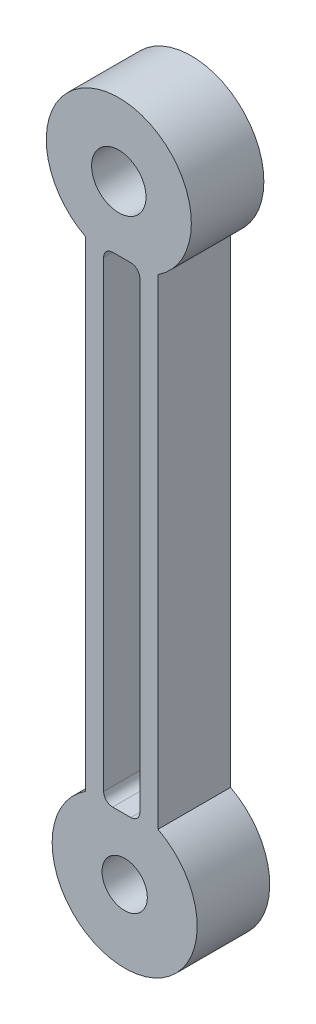
SolidWorks part; units mm, degrees
ref_plane "Front Plane" through (0, 0, 0) normal (0, 0, 1) x (1, 0, 0)
ref_plane "Top Plane" through (0, 0, 0) normal (0, 1, 0) x (1, 0, 0)
ref_plane "Right Plane" through (0, 0, 0) normal (1, 0, 0) x (0, 0, -1)
sketch "Sketch1" plane through (0, 0, 0) normal (0, 0, 1) x (1, 0, 0)
  line L0 (4, 18) -> (4, 71)
  line L1 (-4, 17.6257) -> (-4, 70.6257)
  line L2 (-2, 69.6257) -> (-2, 18.6257)
  line L3 (-1, 70.6257) -> (1, 70.6257)
  line L5 (-1, 0) -> (1, 0)
  line L7 (-1, 17.6257) -> (1, 17.6257)
  line L8 (2, 18.6257) -> (2, 69.6257)
  arc A2 (4, 71) -> (-4, 70.6257) centre (-0.3237, 77.731) ccw
  arc A3 (-4, 17.6257) -> (4, 18) centre (0.3237, 10.8947) ccw
  circle A4 centre (-0.3237, 77.731) radius 3
  circle A5 centre (0.3237, 10.8947) radius 2.5
  circle A7 centre (0.3237, 10.8947) radius 2.5
  arc A8 (-1, 0) -> (-2, 1) centre (-1, 1) cw
  arc A9 (1, 0) -> (2, 1) centre (1, 1) ccw
  arc A10 (1, 70.6257) -> (2, 69.6257) centre (1, 69.6257) cw
  arc A11 (-2, 69.6257) -> (-1, 70.6257) centre (-1, 69.6257) cw
  arc A12 (1, 17.6257) -> (2, 18.6257) centre (1, 18.6257) ccw
  arc A13 (-1, 17.6257) -> (-2, 18.6257) centre (-1, 18.6257) cw
  dimension "D1" = 53
  dimension "D3" = 53
  dimension "D4" = 16
  dimension "D5" = 16
  dimension "D8" = 6
  dimension "D9" = 5
  dimension "D11" = 5
  dimension "D12" = 1
  dimension "D6" = 1
  dimension "D2" = 8
extrude "Boss-Extrude1" add sketch "Sketch1" along normal blind 8
